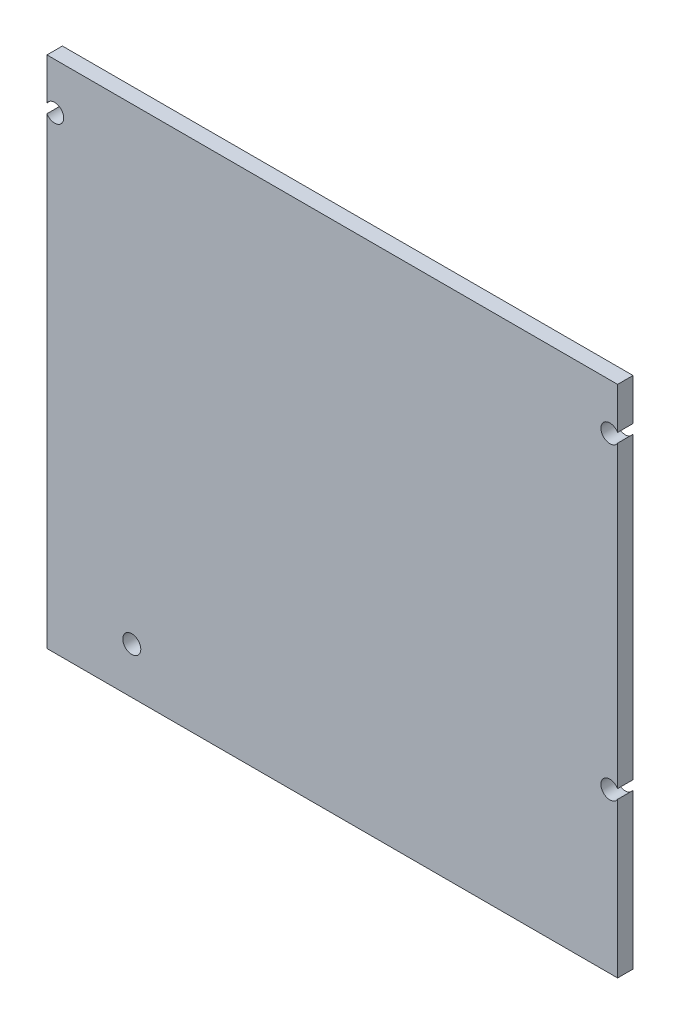
SolidWorks part; units mm, degrees
ref_plane "정면" through (0, 0, 0) normal (0, 0, 1) x (1, 0, 0)
ref_plane "윗면" through (0, 0, 0) normal (0, 1, 0) x (1, 0, 0)
ref_plane "우측면" through (0, 0, 0) normal (1, 0, 0) x (0, 0, -1)
sketch "Sketch1" plane through (0, 0, 0) normal (0, 0, 1) x (1, 0, 0)
  line L0 (4, -91) -> (-112, -91) construction
  line L1 (-109.5, 9) -> (1.5, 9)
  line L2 (-109.5, 9) -> (-109.5, -91)
  line L3 (-109.5, -91) -> (1.5, -91)
  line L4 (1.5, 9) -> (1.5, -91)
  line L5 (-109.5, 9) -> (1.5, -91) construction
  line L6 (-109.5, -91) -> (1.5, 9) construction
  line L7 (-112, 9) -> (4, 9) construction
  line L8 (-117, -86) -> (-117, 4) construction
  line L9 (9, 4) -> (9, -86) construction
  point P0 (-54, -41)
  dimension "D1" = 7.5
  dimension "D2" = 7.5
  dimension "D3" = 100
  dimension "D4" = 111
extrude "Boss-Extrude1" add sketch "Sketch1" along normal blind 3
hole_wizard "Ø3.5 (3.5) Diameter Hole1" positions "Sketch3" profile "Sketch2" hole size "Ø3.5" standard "ANSI Metric" end condition through all
sketch "Sketch3" plane through (0, 0, 3) normal (0, 0, 1) x (1, 0, 0)
  point P0 (0, 0)
  point P3 (-108, 0)
  point P6 (-93, -82)
  point P9 (0, -60)
sketch "Sketch2" plane through (0, 0, 3) normal (1, 0, 0) x (0, -1, 0)
  line L0 (0, 0) -> (0, 3)
  line L1 (0, 3) -> (1.75, 3)
  line L2 (1.75, 3) -> (1.75, 0)
  line L5 (1.75, 0) -> (0, 0)
  line L11 (0, -6.35) -> (0, 107.95) construction
  dimension "Thru Hole Dia." = 3.5
  dimension "Thru Hole Depth" = 3
